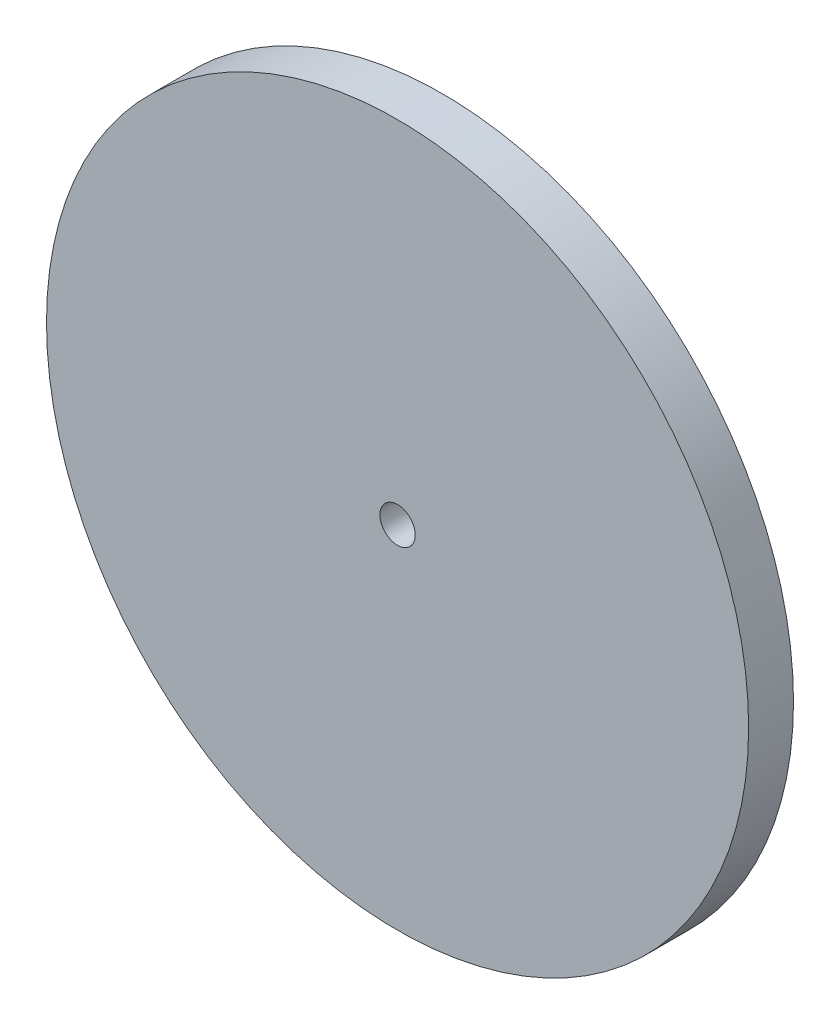
SolidWorks part; units mm, degrees
ref_plane "Front Plane" through (0, 0, 0) normal (0, 0, 1) x (1, 0, 0)
ref_plane "Top Plane" through (0, 0, 0) normal (0, 1, 0) x (1, 0, 0)
ref_plane "Right Plane" through (0, 0, 0) normal (1, 0, 0) x (0, 0, -1)
sketch "Sketch1" plane through (0, 0, 0) normal (0, 0, 1) x (1, 0, 0)
  circle A0 centre (0, 0) radius 39.75
  dimension "D1" = 79.5
extrude "Boss-Extrude1" add sketch "Sketch1" along normal blind 5.08
sketch "Sketch2" plane through (0, 0, 5.08) normal (0, 0, 1) x (1, 0, 0)
  circle A0 centre (0, 0) radius 2
extrude "Cut-Extrude1" cut sketch "Sketch2" against normal blind 10
equation "\"foamcore\"= .1in"
equation "\"MDF\"= .2in"
equation "\"GMaterial\"= \"MDF\""
equation "\"D1@Boss-Extrude1\"=\"GMaterial\""
